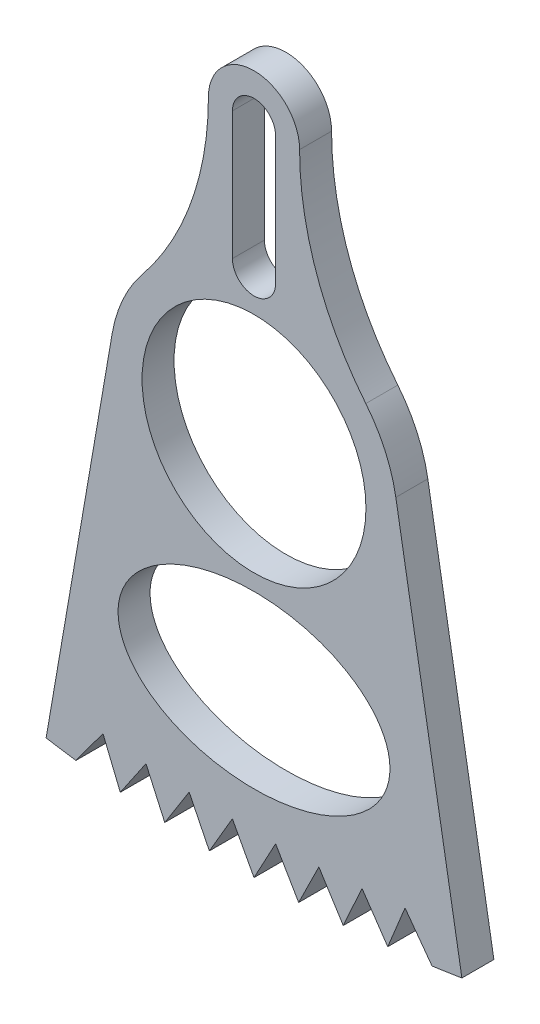
SolidWorks part; units mm, degrees
material "ABS"
ref_plane "Front Plane" through (0, 0, 0) normal (0, 0, 1) x (1, 0, 0)
ref_plane "Top Plane" through (0, 0, 0) normal (0, 1, 0) x (1, 0, 0)
ref_plane "Right Plane" through (0, 0, 0) normal (1, 0, 0) x (0, 0, -1)
sketch "Sketch1" plane through (0, 0, 0) normal (0, 0, 1) x (1, 0, 0)
  line L0 (0, 0) -> (0, -23.5) construction
  line L1 (0, 9.35) -> (0, 17.35) construction
  line L2 (-1.35, 9.35) -> (-1.35, 17.35)
  line L3 (1.35, 9.35) -> (1.35, 17.35)
  line L4 (0, 13.35) -> (-9.1724, -21.636) construction
  line L5 (-13, -22.4367) -> (-8.8692, 1.5287)
  line L6 (13, -22.4367) -> (8.8692, 1.5287)
  line L7 (-2.85, 9.35) -> (-2.85, 17.35) construction
  line L8 (2.85, 9.35) -> (2.85, 17.35) construction
  line L9 (0, 0) -> (7, 0) construction
  line L10 (0, -9.35) -> (0, -17.35) construction
  line L11 (-1.35, -9.35) -> (-1.35, -17.35) construction
  line L12 (1.35, -9.35) -> (1.35, -17.35) construction
  circle A0 centre (0, 0) radius 23.5 construction
  circle A1 centre (0, 0) radius 7
  arc A2 (-1.35, 9.35) -> (1.35, 9.35) centre (0, 9.35) ccw
  arc A3 (1.35, 17.35) -> (-1.35, 17.35) centre (0, 17.35) ccw
  circle A4 centre (0, 0) radius 20 construction
  circle A5 centre (-3.5, 0) radius 1.5 construction
  circle A6 centre (0, 0) radius 6 construction
  circle A7 centre (0, 3.5) radius 1.5 construction
  circle A8 centre (3.5, 0) radius 1.5 construction
  circle A9 centre (0, -3.5) radius 1.5 construction
  arc A10 (-13, -22.4367) -> (13, -22.4367) centre (0, 56.5) ccw
  arc A11 (2.85, 17.35) -> (-2.85, 17.35) centre (0, 17.35) ccw
  arc A12 (-2.85, 9.35) -> (2.85, 9.35) centre (0, 9.35) ccw construction
  circle A13 centre (0, 0) radius 9 construction
  arc A14 (-2.85, 17.35) -> (-6.9908, 5.6682) centre (-21.3984, 17.35) cw
  arc A15 (-6.9908, 5.6682) -> (-8.8692, 1.5287) centre (0, 0) ccw
  arc A16 (6.9908, 5.6682) -> (8.8692, 1.5287) centre (0, 0) cw
  arc A17 (2.85, 17.35) -> (6.9908, 5.6682) centre (21.3984, 17.35) ccw
  arc A18 (-1.35, -9.35) -> (1.35, -9.35) centre (0, -9.35) cw construction
  arc A19 (1.35, -17.35) -> (-1.35, -17.35) centre (0, -17.35) cw construction
  ellipse E0 centre (0, -13.35) end of major axis (-8.5, -13.35) minor radius 5.35
  point P7 (0, 13.35)
  point P16 (-6, 0)
  point P17 (-5, 0)
  point P18 (0, 8)
  point P19 (0, 7)
  point P32 (0, 0)
  point P49 (0, -13.35)
  point P65 (0, -8)
  dimension "D2" = 14
  dimension "D7" = 3
  dimension "D13" = 80
  dimension "D4" = 40
  dimension "D3" = 2.7
  dimension "D5" = 1
  dimension "D6" = 1
  dimension "D10" = 1
  dimension "D12" = 40.85
  dimension "D14" = 26
  dimension "D8" = 7
  dimension "D9" = 8
  dimension "D16" = 2
  dimension "D17" = 13.35
  dimension "D18" = 27
  dimension "D19" = 17
  dimension "D15" = 1.5
  dimension "D11" = 4
extrude "Boss-Extrude1" add sketch "Sketch1" against normal mid plane 2
sketch "Sketch2" plane through (0, 0, 1) normal (0, 0, 1) x (1, 0, 0)
  line L0 (0, 56.5) -> (-13, -22.4367) construction
  line L1 (0, 56.5) -> (13, -22.4367) construction
  line L2 (0, 56.5) -> (0, -23.5) construction
  line L3 (0, 56.5) -> (-1.3962, -23.4878) construction
  line L4 (0, 56.5) -> (-2.792, -23.4513) construction
  line L5 (-2.792, -23.4513) -> (-1.3526, -20.9878)
  line L6 (-1.3526, -20.9878) -> (0, -23.5)
  line L7 (-4.056, -20.8934) -> (-2.792, -23.4513)
  line L8 (-5.5805, -23.3051) -> (-4.056, -20.8934)
  line L9 (-6.7545, -20.7047) -> (-5.5805, -23.3051)
  line L10 (-8.3623, -23.0618) -> (-6.7545, -20.7047)
  line L11 (-9.4448, -20.4219) -> (-8.3623, -23.0618)
  line L12 (-11.1338, -22.7214) -> (-9.4448, -20.4219)
  arc A0 (-2.792, -23.4513) -> (0, -23.5) centre (0, 56.5) ccw
  arc A1 (-13, -22.4367) -> (13, -22.4367) centre (0, 56.5) ccw construction
  circle A2 centre (0, 56.5) radius 80 construction
  arc A3 (-5.5805, -23.3051) -> (-2.792, -23.4513) centre (0, 56.5) ccw
  arc A4 (-8.3623, -23.0618) -> (-5.5805, -23.3051) centre (0, 56.5) ccw
  arc A5 (-11.1338, -22.7214) -> (-8.3623, -23.0618) centre (0, 56.5) ccw
  point P41 (0, 56.5)
  arc M7 (-13, -22.4367) -> (13, -22.4367) centre (0, 56.5) ccw
  dimension "D1" = 18.704
  dimension "D2" = 1
  dimension "D3" = 2
  dimension "D4" = 2.5
  dimension "D5" = 4
extrude "Cut-Extrude1" cut sketch "Sketch2" against normal through all contours L12 L11 M7 | L10 L9 M7 | L8 L7 M7 | L6 L5 M7
mirror "Mirror1" about plane through (0, 0, 0) normal (1, 0, 0) of "Cut-Extrude1"
equation "\"D9@Sketch1\"=\"D8@Sketch1\"+1"
